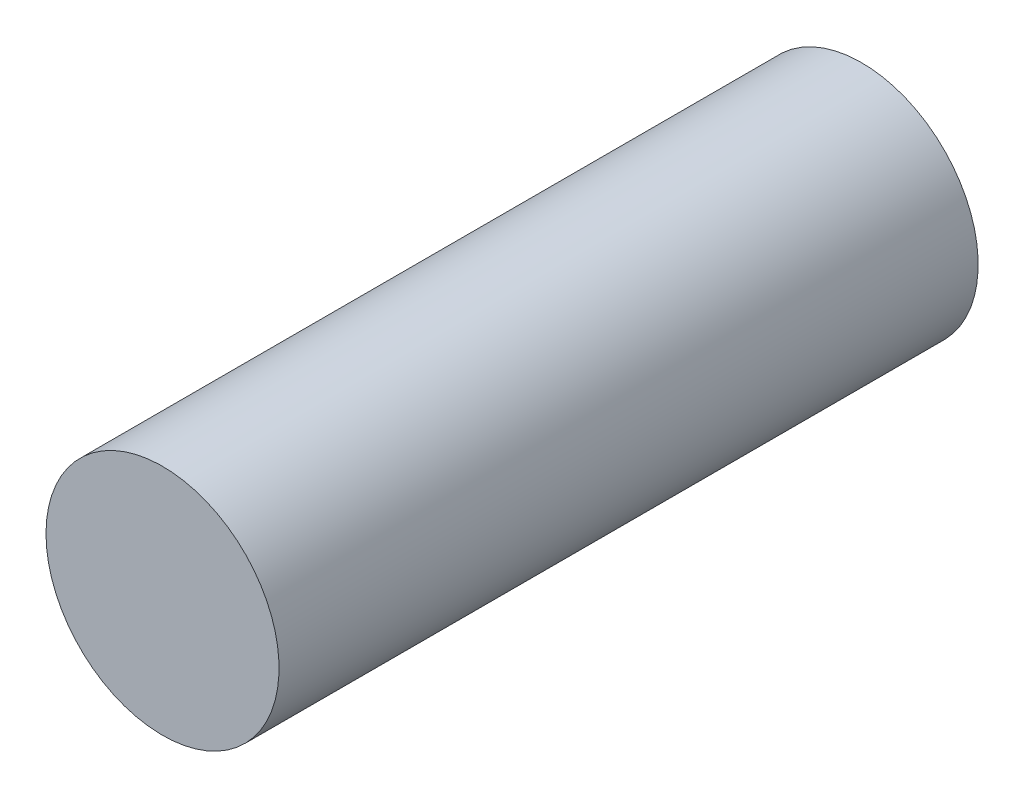
SolidWorks part; units mm, degrees
ref_plane "Front Plane" through (0, 0, 0) normal (0, 0, 1) x (1, 0, 0)
ref_plane "Top Plane" through (0, 0, 0) normal (0, 1, 0) x (1, 0, 0)
ref_plane "Right Plane" through (0, 0, 0) normal (1, 0, 0) x (0, 0, -1)
sketch "Sketch1" plane through (0, 0, 0) normal (0, 0, 1) x (1, 0, 0)
  circle A0 centre (0, 0) radius 3.175
extrude "Boss-Extrude1" add sketch "Sketch1" along normal blind 19.05
